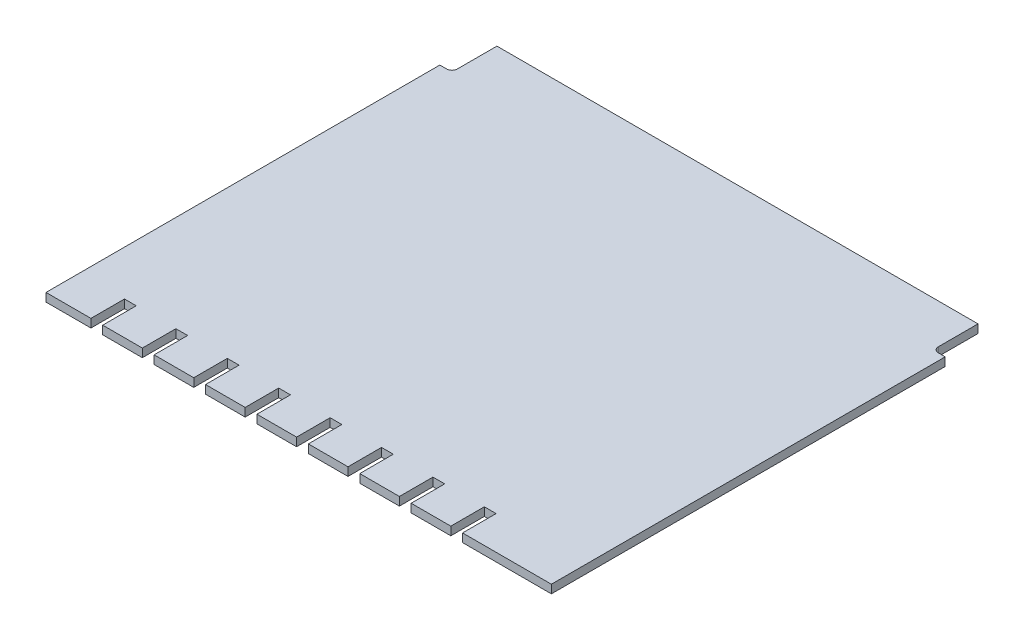
SolidWorks part; units mm, degrees
ref_plane "Front Plane" through (0, 0, 0) normal (0, 0, 1) x (1, 0, 0)
ref_plane "Top Plane" through (0, 0, 0) normal (0, 1, 0) x (1, 0, 0)
ref_plane "Right Plane" through (0, 0, 0) normal (1, 0, 0) x (0, 0, -1)
sketch "Sketch1" plane through (0, 0, 0) normal (0, 1, 0) x (1, 0, 0)
  line L0 (4.5, 75.5) -> (4.5, 83)
  line L1 (2.2, 0) -> (97.8, 0) construction
  line L2 (4.5, 83) -> (95.5, 83)
  line L3 (2.2, 74.5) -> (97.8, 74.5) construction
  line L4 (95.5, 83) -> (95.5, 75.5)
  line L5 (2.2, 74.5) -> (3.5, 74.5)
  line L6 (96.5, 74.5) -> (97.8, 74.5)
  line L7 (10.7, 0) -> (10.7, 6.3449)
  line L8 (10.7, 6.3449) -> (12.925, 6.3449)
  line L9 (12.925, 6.3449) -> (12.925, 0)
  line L10 (12.925, 0) -> (20.425, 0)
  line L11 (20.425, 0) -> (20.425, 6.3449)
  line L12 (20.425, 6.3449) -> (22.65, 6.3449)
  line L13 (22.65, 6.3449) -> (22.65, 0)
  line L14 (22.65, 0) -> (30.15, 0)
  line L15 (30.15, 0) -> (30.15, 6.3449)
  line L16 (2.2, 0) -> (2.2, 74.5)
  line L17 (30.15, 6.3449) -> (32.375, 6.3449)
  line L18 (97.8, 0) -> (97.8, 74.5)
  line L19 (32.375, 6.3449) -> (32.375, 0)
  line L20 (32.375, 0) -> (39.875, 0)
  line L21 (2.2, 0) -> (10.7, 0)
  line L22 (39.875, 0) -> (39.875, 6.3449)
  line L23 (39.875, 6.3449) -> (42.1, 6.3449)
  line L24 (42.1, 6.3449) -> (42.1, 0)
  line L25 (42.1, 0) -> (49.6, 0)
  line L26 (49.6, 0) -> (49.6, 6.3449)
  line L27 (49.6, 6.3449) -> (51.825, 6.3449)
  line L28 (51.825, 6.3449) -> (51.825, 0)
  line L29 (51.825, 0) -> (59.325, 0)
  line L30 (59.325, 0) -> (59.325, 6.3449)
  line L31 (59.325, 6.3449) -> (61.55, 6.3449)
  line L32 (61.55, 6.3449) -> (61.55, 0)
  line L33 (61.55, 0) -> (69.05, 0)
  line L34 (69.05, 0) -> (69.05, 6.3449)
  line L35 (69.05, 6.3449) -> (71.275, 6.3449)
  line L36 (71.275, 6.3449) -> (71.275, 0)
  line L37 (71.275, 0) -> (78.775, 0)
  line L38 (78.775, 0) -> (78.775, 6.3449)
  line L39 (78.775, 6.3449) -> (81, 6.3449)
  line L40 (81, 6.3449) -> (81, 0)
  line L41 (81, 0) -> (97.8, 0)
  line L42 (36.125, 0) -> (36.125, 83) construction
  arc A0 (95.5, 75.5) -> (96.5, 74.5) centre (96.5, 75.5) ccw
  arc A1 (4.5, 75.5) -> (3.5, 74.5) centre (3.5, 75.5) cw
  point P8 (95.5, 74.5)
  point P11 (4.5, 74.5)
  dimension "D1" = 1
extrude "Boss-Extrude1" add sketch "Sketch1" along normal blind 1.5875
ref_plane "center-of-slot" through (0, 0.7937, 0) normal (0, 1, 0) x (1, 0, 0)
ref_plane "Plane1" through (50, 0, 0) normal (-1, 0, 0) x (0, 0, 1)
